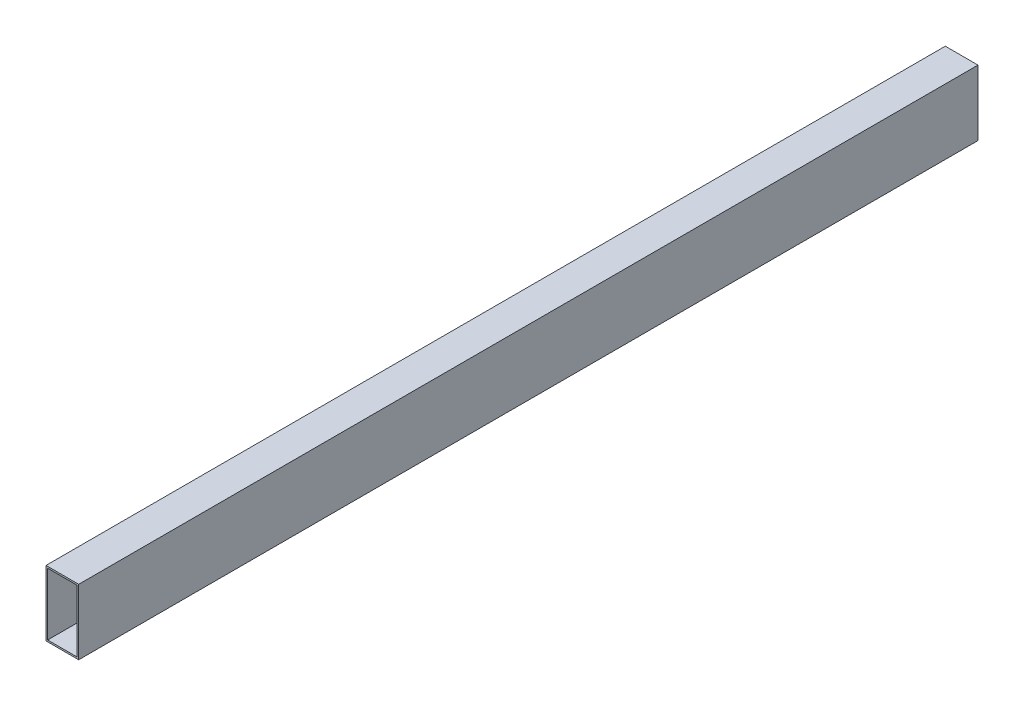
SolidWorks part; units mm, degrees
material "1060 合金"
ref_plane "前视基准面" through (0, 0, 0) normal (0, 0, 1) x (1, 0, 0)
ref_plane "上视基准面" through (0, 0, 0) normal (0, 1, 0) x (1, 0, 0)
ref_plane "右视基准面" through (0, 0, 0) normal (1, 0, 0) x (0, 0, -1)
other "Configuration Table"
sketch "草图1" plane through (0, 0, 0) normal (0, 0, 1) x (1, 0, 0)
  line L1 (0, 0) -> (20, 0)
  line L2 (0, 0) -> (0, -40)
  line L3 (0, -40) -> (20, -40)
  line L4 (20, 0) -> (20, -40)
  dimension "D1" = 40
  dimension "D2" = 20
extrude "拉伸-薄壁1" add sketch "草图1" along normal blind 550 thin
